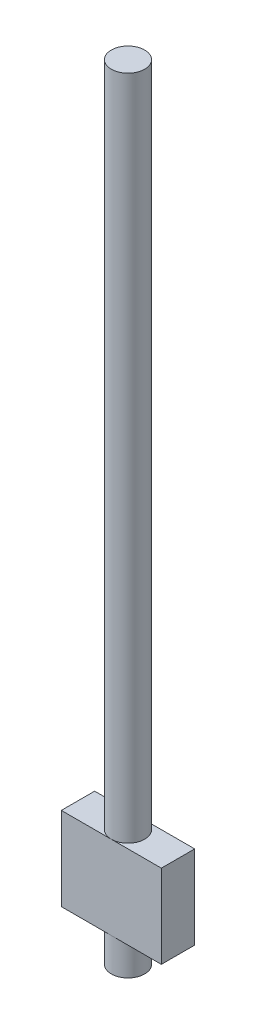
SolidWorks part; units mm, degrees
ref_plane "Front Plane" through (0, 0, 0) normal (0, 0, 1) x (1, 0, 0)
ref_plane "Top Plane" through (0, 0, 0) normal (0, 1, 0) x (1, 0, 0)
ref_plane "Right Plane" through (0, 0, 0) normal (1, 0, 0) x (0, 0, -1)
sketch "Sketch1" plane through (0, 0, 0) normal (0, 1, 0) x (1, 0, 0)
  line L0 (-1.5, -0.5) -> (-1.5, 0.5)
  line L1 (-1.5, -0.5) -> (1.5, -0.5)
  line L2 (-1.5, 0.5) -> (1.5, 0.5)
  line L3 (1.5, -0.5) -> (1.5, 0.5)
  line L4 (-1.5, -0.5) -> (1.5, 0.5) construction
  line L5 (-1.5, 0.5) -> (1.5, -0.5) construction
  point P1 (0, 0)
  dimension "D1" = 3
  dimension "D2" = 1
extrude "Boss-Extrude1" add sketch "Sketch1" along normal blind 2.5
sketch "Sketch2" plane through (0, 2.5, 0) normal (0, 1, 0) x (1, 0, 0)
  circle A0 centre (0, 0) radius 0.5
  dimension "D1" = 1
extrude "Boss-Extrude2" add sketch "Sketch2" along normal blind 20
sketch "Sketch3" plane through (0, 0, 0) normal (0, -1, 0) x (1, 0, 0)
  circle A0 centre (0, 0) radius 0.5
  dimension "D1" = 1
extrude "Boss-Extrude3" add sketch "Sketch3" along normal blind 1
